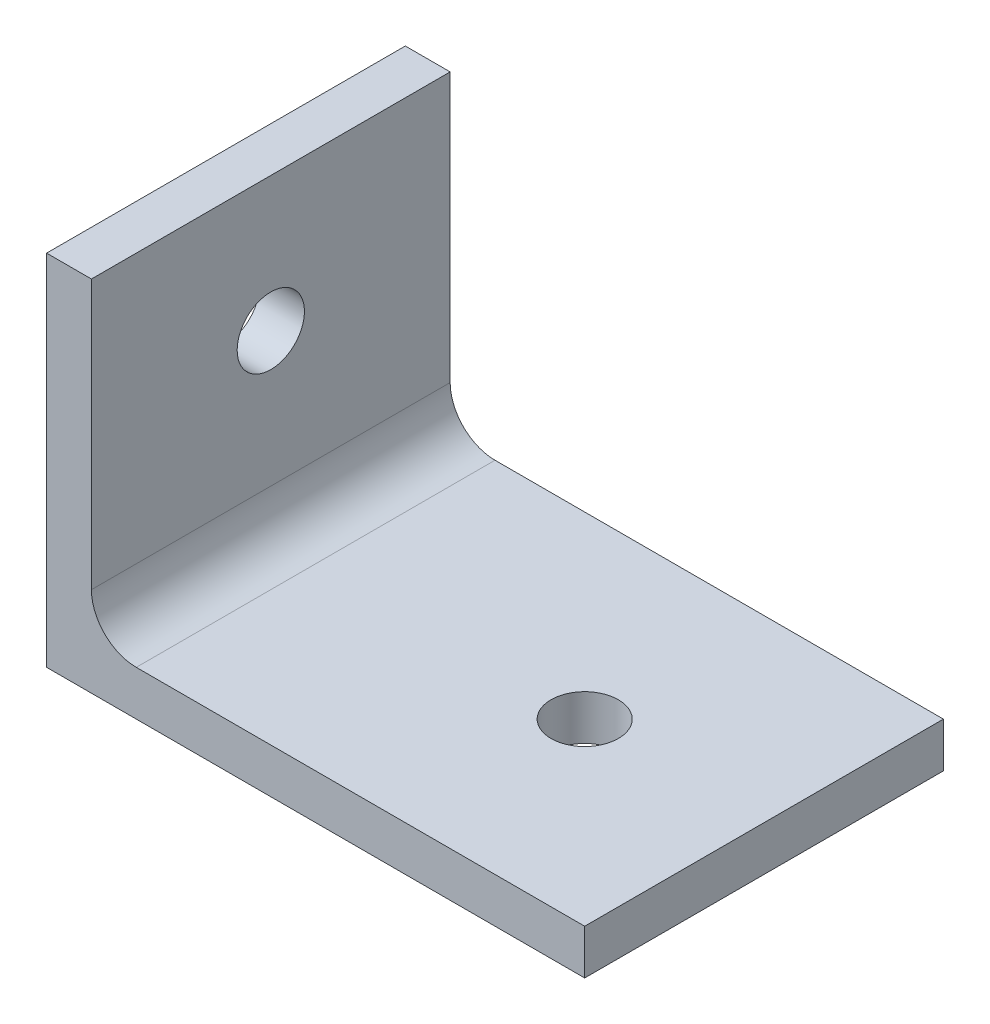
SolidWorks part; units mm, degrees
material "6061 Alloy"
ref_plane "Front Plane" through (0, 0, 0) normal (0, 0, 1) x (1, 0, 0)
ref_plane "Top Plane" through (0, 0, 0) normal (0, 1, 0) x (1, 0, 0)
ref_plane "Right Plane" through (0, 0, 0) normal (1, 0, 0) x (0, 0, -1)
sketch "Sketch1" plane through (0, 0, 0) normal (0, 0, 1) x (1, 0, 0)
  line L0 (0, 0) -> (76.2, 0)
  line L1 (76.2, 0) -> (76.2, 6.35)
  line L2 (76.2, 6.35) -> (6.35, 6.35)
  line L3 (6.35, 6.35) -> (6.35, 50.8)
  line L4 (6.35, 50.8) -> (0, 50.8)
  line L5 (0, 50.8) -> (0, 0)
  dimension "D1" = 76.2
  dimension "D2" = 6.35
  dimension "D4" = 44.45
  dimension "D5" = 6.35
extrude "Bracket" add sketch "Sketch1" along normal mid plane 50.8
fillet "Fillet" radius 6.35 1 edges at (6.35, 6.35, 0)
sketch "Sketch2" plane through (0, 6.35, 0) normal (0, 1, 0) x (1, 0, 0)
  line L0 (76.2, 25.4) -> (12.7, 25.4) construction
  line L1 (76.2, -25.4) -> (76.2, 25.4) construction
  circle A0 centre (50.8, 0) radius 4.7625
  dimension "D1" = 25.4
  dimension "D3" = 9.525
  dimension "D2" = 25.4
extrude "Base hole" cut sketch "Sketch2" against normal through all
sketch "Sketch4" plane through (0, 0, 0) normal (-1, 0, 0) x (0, 0, 1)
  line L0 (25.4, 50.8) -> (-25.4, 50.8) construction
  line L1 (25.4, 50.8) -> (25.4, 0) construction
  circle A0 centre (0, 31.75) radius 4.7625
  dimension "D1" = 9.525
  dimension "D2" = 19.05
  dimension "D3" = 25.4
extrude "Cut-Extrude2" cut sketch "Sketch4" against normal through all
